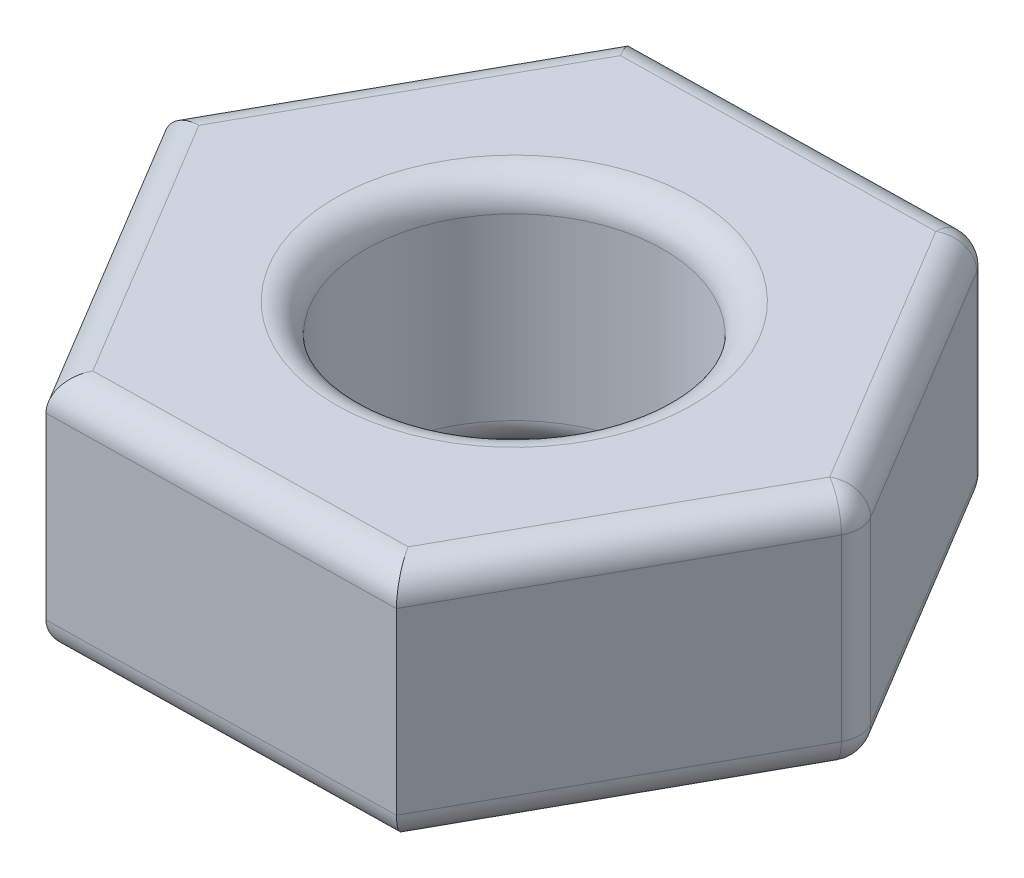
SolidWorks part; units mm, degrees
ref_plane "前视基准面" through (0, 0, 0) normal (0, 0, 1) x (1, 0, 0)
ref_plane "上视基准面" through (0, 0, 0) normal (0, 1, 0) x (1, 0, 0)
ref_plane "右视基准面" through (0, 0, 0) normal (1, 0, 0) x (0, 0, -1)
sketch "草图1" plane through (0, 0, 0) normal (0, 1, 0) x (1, 0, 0)
  line L1 (1.1197, 2.0198) -> (-1.1894, 1.9796)
  line L2 (-1.1894, 1.9796) -> (-2.3091, -0.0402)
  line L3 (-2.3091, -0.0402) -> (-1.1197, -2.0198)
  line L4 (-1.1197, -2.0198) -> (1.1894, -1.9796)
  line L5 (1.1894, -1.9796) -> (2.3091, 0.0402)
  line L6 (2.3091, 0.0402) -> (1.1197, 2.0198)
  circle A0 centre (0, 0) radius 2 construction
  circle A1 centre (0, 0) radius 1
  dimension "D2" = 2
  dimension "D1" = 4
extrude "凸台-拉伸1" add sketch "草图1" along normal blind 1.6
fillet "圆角1" radius 0.2 16 edges at (-0.0348, 0, -1.9997) (-1.7492, 0, -0.9697) (-1.7144, 0, 1.03) (0.0348, 0, 1.9997) (1.7492, 0, 0.9697) (1.7144, 0, -1.03) (0, 1.6, 1) (1.7492, 1.6, 0.9697) (0.0348, 1.6, 1.9997) (-1.7144, 1.6, 1.03) (-1.7492, 1.6, -0.9697) (-0.0348, 1.6, -1.9997) (1.7144, 1.6, -1.03) (2.3091, 0.8, -0.0402) (1.1197, 0.8, -2.0198) (0, 0, 1)
